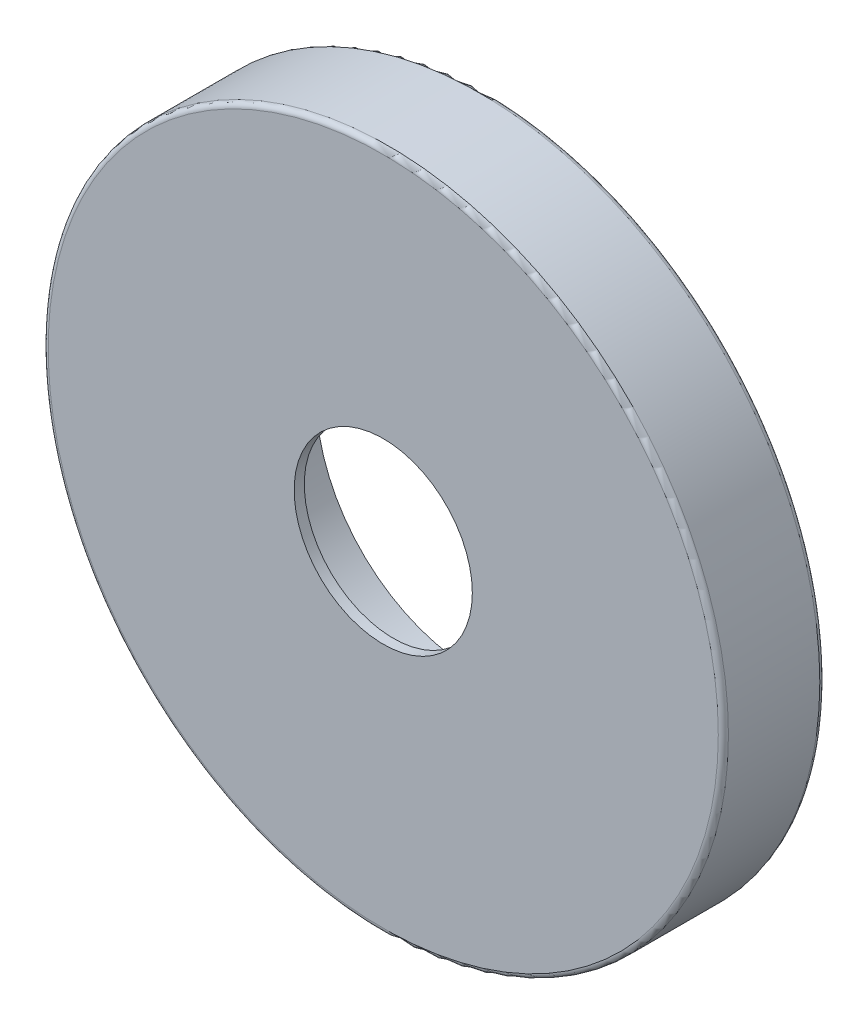
SolidWorks part; units mm, degrees
ref_plane "前视基准面" through (0, 0, 0) normal (0, 0, 1) x (1, 0, 0)
ref_plane "上视基准面" through (0, 0, 0) normal (0, 1, 0) x (1, 0, 0)
ref_plane "右视基准面" through (0, 0, 0) normal (1, 0, 0) x (0, 0, -1)
sketch "草图1" plane through (0, 0, 0) normal (0, 0, 1) x (1, 0, 0)
  circle A0 centre (0, 0) radius 67
  circle A3 centre (0, 0) radius 17.55
  dimension "D1" = 35.1
  dimension "D2" = 134
extrude "凸台-拉伸1" add sketch "草图1" along normal blind 2
sketch "草图2" plane through (0, 0, 0) normal (0, 0, -1) x (-1, 0, 0)
  circle A0 centre (0, 0) radius 31.2
  circle A1 centre (0, 0) radius 31 construction
  circle A2 centre (0, 0) radius 67
  circle A3 centre (0, 0) radius 67 construction
  dimension "D1" = 0.2
extrude "凸台-拉伸2" add sketch "草图2" along normal blind 18
fillet "圆角1" radius 1 1 edges at (67, 0, 2)
shell "抽壳4" thickness 2.5
sketch "草图4" plane through (0, 0, 0) normal (0, 0, -1) x (-1, 0, 0)
  line L0 (-78.8044, 0) -> (78.8044, 0) construction
  line L1 (0, 71.8204) -> (0, -71.8204) construction
  line L6 (-41.0574, 49.7447) -> (-20.0302, 27.1013)
  line L7 (-49.7447, 41.0574) -> (-27.0271, 20.1302)
  line L8 (22.5515, 60.4291) -> (13.4553, 30.8973)
  line L9 (10.6844, 63.6089) -> (3.9198, 33.4713)
  line L10 (63.6089, 10.6844) -> (33.4855, 3.796)
  line L11 (60.4291, 22.5515) -> (30.9468, 13.341)
  line L12 (41.0574, -49.7447) -> (20.0302, -27.1013)
  line L13 (49.7447, -41.0574) -> (27.0271, -20.1302)
  line L14 (-22.5515, -60.4291) -> (-13.4553, -30.8973)
  line L15 (-10.6844, -63.6089) -> (-3.9198, -33.4713)
  line L16 (-63.6089, -10.6844) -> (-33.4855, -3.796)
  line L17 (-60.4291, -22.5515) -> (-30.9468, -13.341)
  circle A0 centre (-34, 34) radius 0.85
  circle A12 centre (12.4449, 46.4449) radius 0.85
  arc A13 (13.4553, 30.8973) -> (3.9198, 33.4713) centre (0, 0) ccw
  arc A15 (22.5515, 60.4291) -> (10.6844, 63.6089) centre (0, 0) ccw
  arc A17 (-20.0302, 27.1013) -> (-27.0271, 20.1302) centre (0, 0) ccw
  arc A18 (-41.0574, 49.7447) -> (-49.7447, 41.0574) centre (0, 0) ccw
  circle A19 centre (46.4449, 12.4449) radius 0.85
  arc A20 (33.4855, 3.796) -> (30.9468, 13.341) centre (0, 0) ccw
  arc A21 (63.6089, 10.6844) -> (60.4291, 22.5515) centre (0, 0) ccw
  circle A22 centre (34, -34) radius 0.85
  arc A23 (20.0302, -27.1013) -> (27.0271, -20.1302) centre (0, 0) ccw
  arc A24 (41.0574, -49.7447) -> (49.7447, -41.0574) centre (0, 0) ccw
  circle A25 centre (-12.4449, -46.4449) radius 0.85
  arc A26 (-13.4553, -30.8973) -> (-3.9198, -33.4713) centre (0, 0) ccw
  arc A27 (-22.5515, -60.4291) -> (-10.6844, -63.6089) centre (0, 0) ccw
  circle A28 centre (-46.4449, -12.4449) radius 0.85
  arc A29 (-33.4855, -3.796) -> (-30.9468, -13.341) centre (0, 0) ccw
  arc A30 (-63.6089, -10.6844) -> (-60.4291, -22.5515) centre (0, 0) ccw
  circle A33 centre (0, 0) radius 64.5 construction
  circle A34 centre (0, 0) radius 33.7 construction
  point P7 (12.4449, 46.4449)
  point P8 (-34, 34)
  point P13 (0, 0)
  point P17 (0, 0)
  point P24 (46.4449, 12.4449)
  point P31 (0, 0)
  point P35 (34, -34)
  point P42 (-12.4449, -46.4449)
  point P43 (0, 0)
  point P50 (-46.4449, -12.4449)
  point P56 (0, 0)
  dimension "D1" = 1.7
  dimension "D2" = 34
  dimension "D3" = 34
  dimension "D4" = 6
extrude "凸台-拉伸3" add sketch "草图4" along normal up to surface (18 mm away) up to face at (-64.5, 0, -18)
fillet "圆角2" radius 1 1 edges at (-67, 0, -18)
sketch "草图5" plane through (0, 0, -0.5) normal (0, 0, -1) x (-1, 0, 0)
  line L0 (-63.6089, -10.6844) -> (-33.4855, -3.796) construction
  line L1 (-27.0271, 20.1302) -> (-49.7447, 41.0574) construction
  line L2 (-41.0574, 49.7447) -> (-20.0302, 27.1013) construction
  line L3 (3.9198, 33.4713) -> (10.6844, 63.6089) construction
  line L4 (30.9468, 13.341) -> (60.4291, 22.5515) construction
  line L5 (22.5515, 60.4291) -> (13.4553, 30.8973) construction
  line L6 (27.0271, -20.1302) -> (49.7447, -41.0574) construction
  line L7 (63.6089, 10.6844) -> (33.4855, 3.796) construction
  line L8 (-3.9198, -33.4713) -> (-10.6844, -63.6089) construction
  line L9 (41.0574, -49.7447) -> (20.0302, -27.1013) construction
  line L10 (-30.9468, -13.341) -> (-60.4291, -22.5515) construction
  line L11 (-22.5515, -60.4291) -> (-13.4553, -30.8973) construction
  line L12 (-63.6089, -10.6844) -> (-33.4855, -3.796)
  line L13 (-27.0271, 20.1302) -> (-49.7447, 41.0574)
  line L14 (-41.0574, 49.7447) -> (-20.0302, 27.1013)
  line L15 (3.9198, 33.4713) -> (10.6844, 63.6089)
  line L16 (30.9468, 13.341) -> (60.4291, 22.5515)
  line L17 (22.5515, 60.4291) -> (13.4553, 30.8973)
  line L18 (27.0271, -20.1302) -> (49.7447, -41.0574)
  line L19 (63.6089, 10.6844) -> (33.4855, 3.796)
  line L20 (-3.9198, -33.4713) -> (-10.6844, -63.6089)
  line L21 (41.0574, -49.7447) -> (20.0302, -27.1013)
  line L22 (-30.9468, -13.341) -> (-60.4291, -22.5515)
  line L23 (-22.5515, -60.4291) -> (-13.4553, -30.8973)
  arc A0 (-27.0271, 20.1302) -> (-33.4855, -3.796) centre (0, 0) ccw construction
  arc A1 (-49.7447, 41.0574) -> (-63.6089, -10.6844) centre (0, 0) ccw construction
  arc A2 (3.9198, 33.4713) -> (-20.0302, 27.1013) centre (0, 0) ccw construction
  arc A3 (10.6844, 63.6089) -> (-41.0574, 49.7447) centre (0, 0) ccw construction
  arc A4 (60.4291, 22.5515) -> (22.5515, 60.4291) centre (0, 0) ccw construction
  arc A5 (30.9468, 13.341) -> (13.4553, 30.8973) centre (0, 0) ccw construction
  arc A6 (49.7447, -41.0574) -> (63.6089, 10.6844) centre (0, 0) ccw construction
  arc A7 (27.0271, -20.1302) -> (33.4855, 3.796) centre (0, 0) ccw construction
  arc A8 (-10.6844, -63.6089) -> (41.0574, -49.7447) centre (0, 0) ccw construction
  arc A9 (-3.9198, -33.4713) -> (20.0302, -27.1013) centre (0, 0) ccw construction
  arc A10 (-60.4291, -22.5515) -> (-22.5515, -60.4291) centre (0, 0) ccw construction
  arc A11 (-30.9468, -13.341) -> (-13.4553, -30.8973) centre (0, 0) ccw construction
  arc A12 (-27.0271, 20.1302) -> (-33.4855, -3.796) centre (0, 0) ccw
  arc A13 (-49.7447, 41.0574) -> (-63.6089, -10.6844) centre (0, 0) ccw
  arc A14 (3.9198, 33.4713) -> (-20.0302, 27.1013) centre (0, 0) ccw
  arc A15 (10.6844, 63.6089) -> (-41.0574, 49.7447) centre (0, 0) ccw
  arc A16 (60.4291, 22.5515) -> (22.5515, 60.4291) centre (0, 0) ccw
  arc A17 (30.9468, 13.341) -> (13.4553, 30.8973) centre (0, 0) ccw
  arc A18 (49.7447, -41.0574) -> (63.6089, 10.6844) centre (0, 0) ccw
  arc A19 (27.0271, -20.1302) -> (33.4855, 3.796) centre (0, 0) ccw
  arc A20 (-10.6844, -63.6089) -> (41.0574, -49.7447) centre (0, 0) ccw
  arc A21 (-3.9198, -33.4713) -> (20.0302, -27.1013) centre (0, 0) ccw
  arc A22 (-60.4291, -22.5515) -> (-22.5515, -60.4291) centre (0, 0) ccw
  arc A23 (-30.9468, -13.341) -> (-13.4553, -30.8973) centre (0, 0) ccw
extrude "切除-拉伸1" cut sketch "草图5" against normal blind 1.2
sketch "草图6" plane through (0, 0, -18) normal (0, 0, -1) x (-1, 0, 0)
  circle A0 centre (0, 0) radius 64.5
extrude "切除-拉伸2" cut sketch "草图6" against normal blind 2
